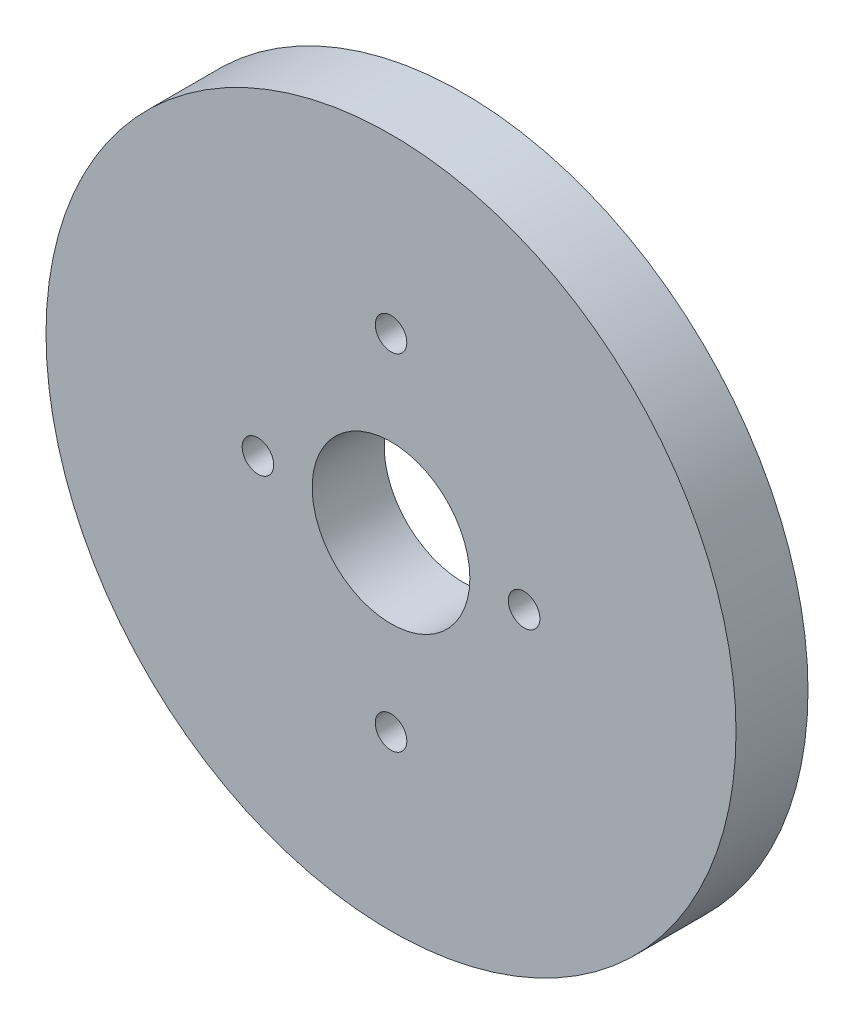
SolidWorks part; units mm, degrees
ref_plane "Front Plane" through (0, 0, 0) normal (0, 0, 1) x (1, 0, 0)
ref_plane "Top Plane" through (0, 0, 0) normal (0, 1, 0) x (1, 0, 0)
ref_plane "Right Plane" through (0, 0, 0) normal (1, 0, 0) x (0, 0, -1)
sketch "Sketch1" plane through (0, 0, 0) normal (0, 0, 1) x (1, 0, 0)
  line L0 (0, 0) -> (0, 8.75) construction
  line L1 (0, 0) -> (6.75, 0) construction
  circle A0 centre (0, 0) radius 17.5
  circle A1 centre (0, 0) radius 4
  circle A2 centre (6.75, 0) radius 0.8
  circle A3 centre (0, 8.75) radius 0.8
  circle A4 centre (0, -8.75) radius 0.8
  circle A5 centre (-6.75, 0) radius 0.8
  dimension "D1" = 35
  dimension "D2" = 8
  dimension "D3" = 1.6
  dimension "D4" = 6.75
  dimension "D5" = 8.75
extrude "Boss-Extrude1" add sketch "Sketch1" along normal blind 3.65
